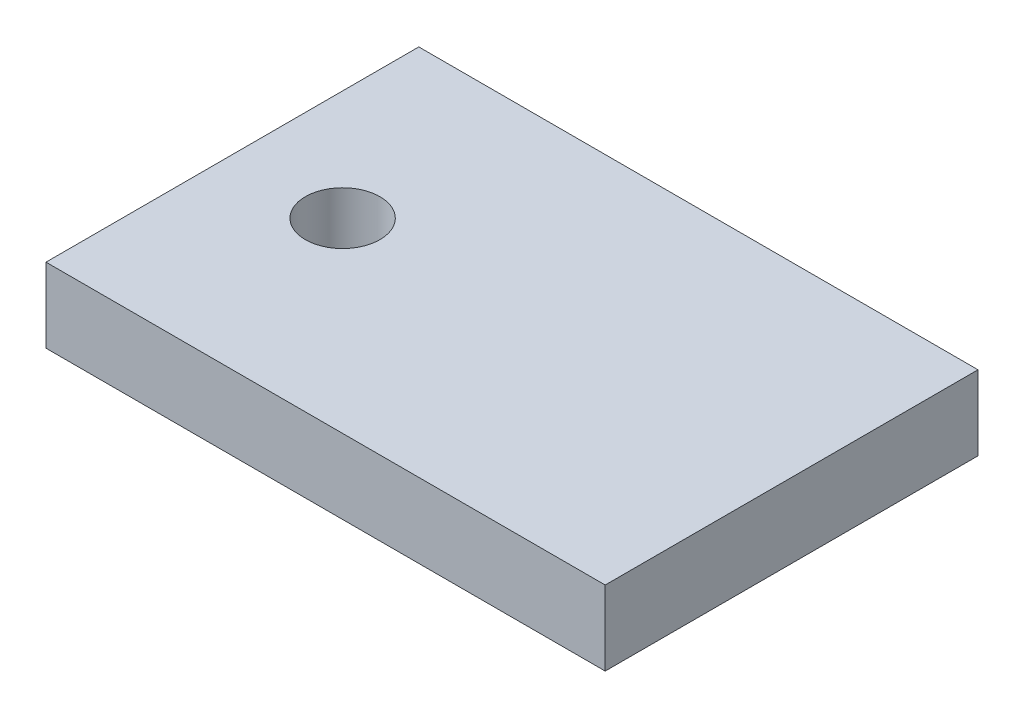
SolidWorks part; units mm, degrees
ref_plane "Спереди" through (0, 0, 0) normal (0, 0, 1) x (1, 0, 0)
ref_plane "Сверху" through (0, 0, 0) normal (0, 1, 0) x (1, 0, 0)
ref_plane "Справа" through (0, 0, 0) normal (1, 0, 0) x (0, 0, -1)
sketch "Эскиз1" plane through (0, 0, 0) normal (1, 0, 0) x (0, 0, -1)
  line L1 (0, 0) -> (30, 0)
  line L2 (0, 0) -> (0, -6)
  line L3 (0, -6) -> (30, -6)
  line L4 (30, 0) -> (30, -6)
extrude "Вытянуть1" add sketch "Эскиз1" along normal blind 45
sketch "Эскиз2" plane through (0, 0, 0) normal (0, 1, 0) x (-1, 0, 0)
  line L0 (-10.5597, -15) -> (-7.257, -15) construction
  circle A0 centre (-8.8699, -15) radius 3
extrude "Вырез-Вытянуть1" cut sketch "Эскиз2" against normal through all
